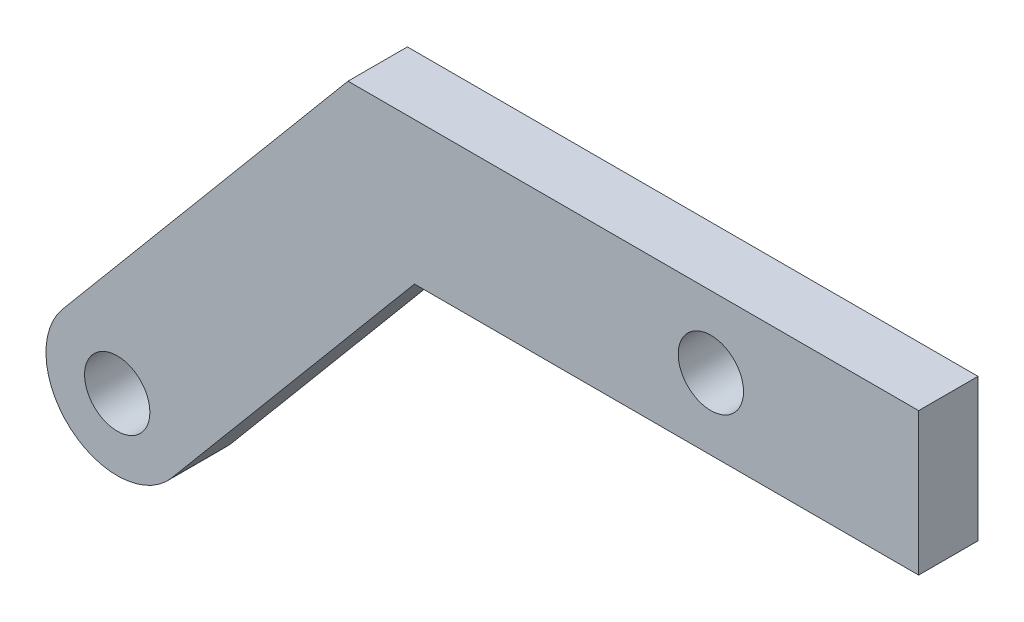
SolidWorks part; units mm, degrees
ref_plane "Front Plane" through (0, 0, 0) normal (0, 0, 1) x (1, 0, 0)
ref_plane "Top Plane" through (0, 0, 0) normal (0, 1, 0) x (1, 0, 0)
ref_plane "Right Plane" through (0, 0, 0) normal (1, 0, 0) x (0, 0, -1)
sketch "Sketch1" plane through (0, 0, 0) normal (0, 0, 1) x (1, 0, 0)
  line L0 (0, 0) -> (41.8412, 0)
  line L1 (-9.1925, 7.7135) -> (38.8766, 65)
  line L2 (9.1925, -7.7135) -> (50.068, 41)
  line L3 (38.8766, 65) -> (135, 65)
  line L4 (135, 65) -> (135, 41)
  line L5 (135, 41) -> (50.068, 41)
  line L6 (9.1925, -7.7135) -> (57.2617, 49.5731) construction
  circle A0 centre (0, 0) radius 5.5
  circle A1 centre (0, 0) radius 12
  circle A2 centre (100, 53) radius 5.5
  dimension "D1" = 50
  dimension "D3" = 11
  dimension "D4" = 24
  dimension "D7" = 35
  dimension "D2" = 65
  dimension "D6" = 24
  dimension "D8" = 135
  dimension "D9" = 12
  dimension "D5" = 24
extrude "Boss-Extrude1" add sketch "Sketch1" along normal blind 10
